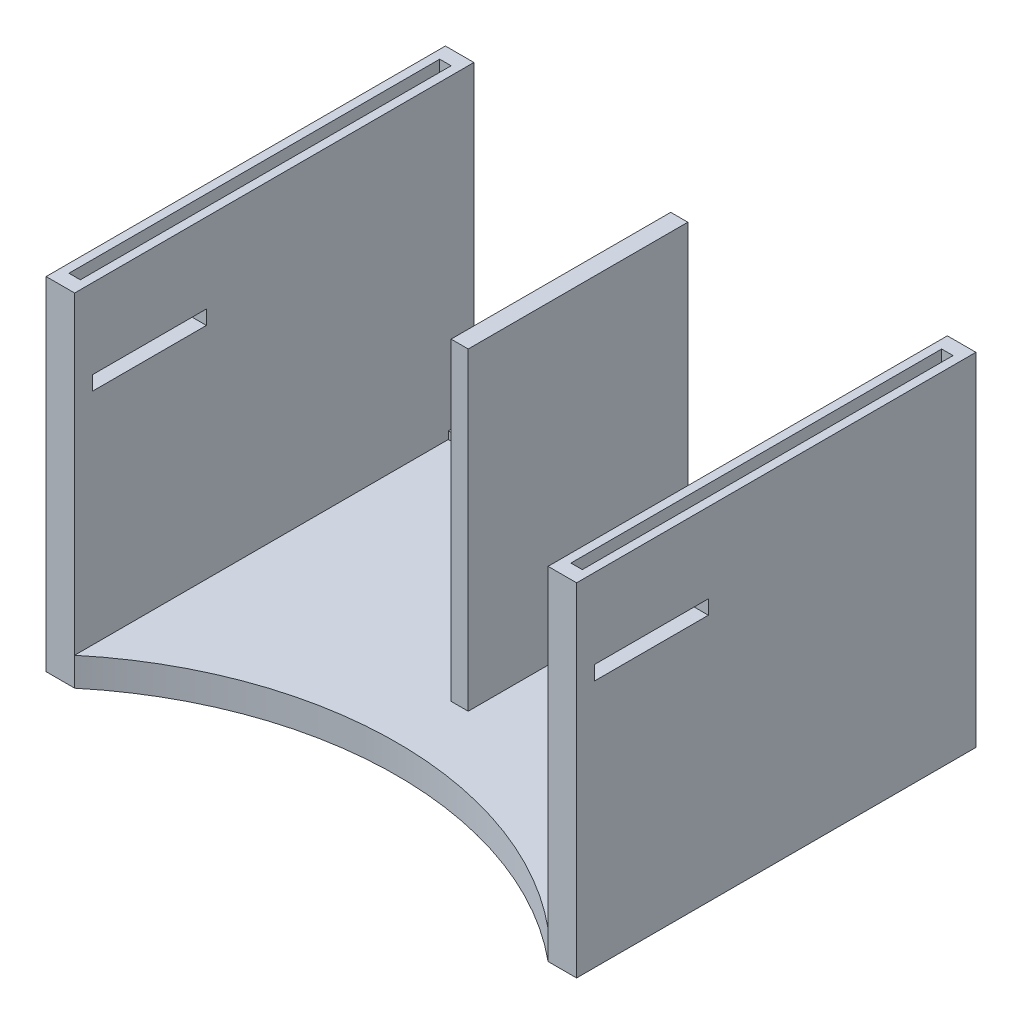
SolidWorks part; units mm, degrees
ref_plane "Front Plane" through (0, 0, 0) normal (0, 0, 1) x (1, 0, 0)
ref_plane "Top Plane" through (0, 0, 0) normal (0, 1, 0) x (1, 0, 0)
ref_plane "Right Plane" through (0, 0, 0) normal (1, 0, 0) x (0, 0, -1)
sketch "Sketch2" plane through (0, 0, 0) normal (0, 0, 1) x (1, 0, 0)
  line L0 (0, 0) -> (186, 0)
  line L1 (186, 0) -> (186, 120)
  line L2 (0, 0) -> (0, 120)
  dimension "D1" = 120
  dimension "D2" = 186
extrude "Extrude-Thin2" add sketch "Sketch2" along normal blind 140 thin thin type one direction wall 10
sketch "Sketch11" plane through (0, 10, 0) normal (0, 1, 0) x (1, 0, 0)
  line L0 (10, -140) -> (10, 0) construction
  line L1 (10, -4) -> (176, -4)
  line L2 (10, -4) -> (10, -9)
  line L3 (10, -9) -> (176, -9)
  line L4 (176, -4) -> (176, -9)
  line L5 (176, -140) -> (176, 0) construction
  line L6 (176, 0) -> (10, 0) construction
  dimension "D1" = 4
  dimension "D2" = 5
extrude "Boss-Extrude3" add sketch "Sketch11" along normal blind 2.6416
sketch "Sketch13" plane through (10, 0, 0) normal (1, 0, 0) x (0, 0, -1)
  line L1 (-133.795, 92.0516) -> (-93.795, 92.0516)
  line L2 (-133.795, 92.0516) -> (-133.795, 87.0516)
  line L3 (-133.795, 87.0516) -> (-93.795, 87.0516)
  line L4 (-93.795, 92.0516) -> (-93.795, 87.0516)
  dimension "D1" = 5
  dimension "D2" = 40
extrude "Cut-Extrude6" cut sketch "Sketch13" against normal through all both and the other way through all
sketch "Sketch14" plane through (0, 10, 0) normal (0, 1, 0) x (1, 0, 0)
  line L0 (176, -140) -> (10, -140)
  line L1 (93, -110) -> (10, -110) construction
  line L2 (10, -140) -> (10, -9) construction
  arc A0 (10, -140) -> (176, -140) centre (93, -239.8167) cw
  dimension "D1" = 30
extrude "Cut-Extrude7" cut sketch "Sketch14" against normal through all
sketch "Sketch19" plane through (0, 120, 0) normal (0, 1, 0) x (1, 0, 0)
  line L0 (10, -140) -> (10, -9) construction
  line L1 (3, -5) -> (7, -5)
  line L2 (3, -5) -> (3, -135)
  line L3 (3, -135) -> (7, -135)
  line L4 (7, -5) -> (7, -135)
  line L5 (0, -140) -> (0, 0) construction
  line L6 (0, 0) -> (10, 0) construction
  line L7 (0, -140) -> (10, -140) construction
  point P9 (5, 0)
  point P12 (5, -140)
  dimension "D1" = 3
  dimension "D2" = 3
  dimension "D3" = 5
  dimension "D4" = 5
extrude "Cut-Extrude9" cut sketch "Sketch19" against normal blind 10
sketch "Sketch20" plane through (0, 120, 0) normal (0, 1, 0) x (1, 0, 0)
  line L0 (186, -140) -> (186, 0) construction
  line L1 (179, -5) -> (183, -5)
  line L2 (179, -5) -> (179, -135)
  line L3 (179, -135) -> (183, -135)
  line L4 (183, -5) -> (183, -135)
  line L5 (176, -140) -> (176, 0) construction
  line L6 (176, 0) -> (186, 0) construction
  line L7 (176, -140) -> (186, -140) construction
  point P9 (181, 0)
  point P12 (181, -140)
  dimension "D1" = 3
  dimension "D2" = 3
  dimension "D3" = 5
  dimension "D4" = 5
extrude "Cut-Extrude10" cut sketch "Sketch20" against normal blind 10
sketch "Sketch21" plane through (0, 10, 0) normal (0, 1, 0) x (1, 0, 0)
  line L0 (176, -140) -> (176, -9) construction
  line L1 (90, -11) -> (96, -11)
  line L2 (90, -11) -> (90, -88)
  line L3 (90, -88) -> (96, -88)
  line L4 (96, -11) -> (96, -88)
  line L5 (10, -140) -> (10, 0) construction
  line L7 (10, -133.795) -> (10, -93.795) construction
  line L8 (10, -93.795) -> (176, -93.795) construction
  line L9 (10, -140) -> (10, -9) construction
  line L10 (0, -140) -> (10, -140) construction
  line L11 (10, -9) -> (176, -9) construction
  dimension "D1" = 80
  dimension "D2" = 80
  dimension "D3" = 52
  dimension "D4" = 46.205
  dimension "D5" = 2
extrude "Boss-Extrude4" add sketch "Sketch21" along direction (0, 1, 0) on the side of the normal through all
